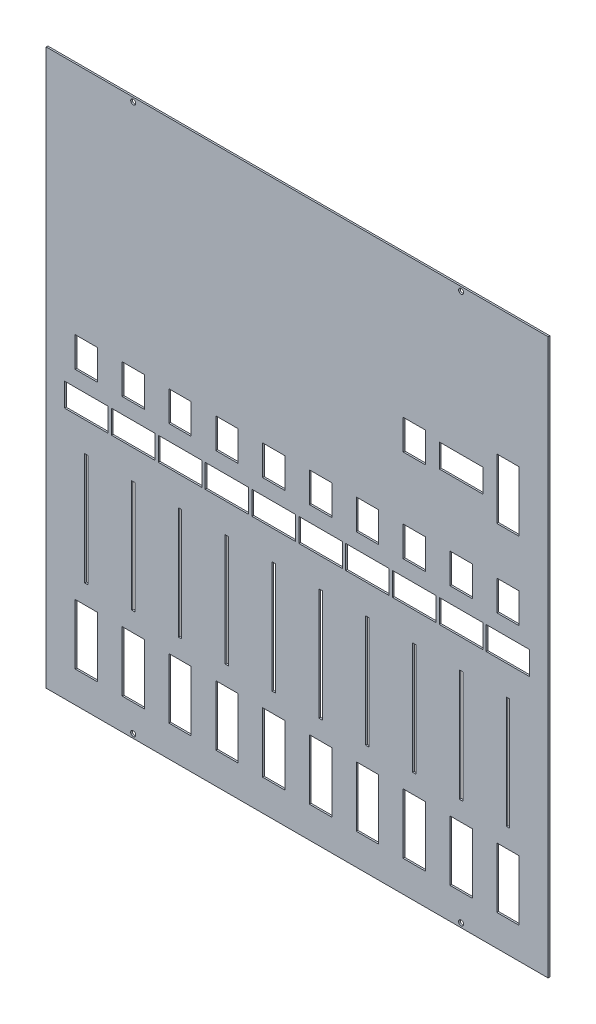
SolidWorks part; units mm, degrees
ref_plane "Front Plane" through (0, 0, 0) normal (0, 0, 1) x (1, 0, 0)
ref_plane "Top Plane" through (0, 0, 0) normal (0, 1, 0) x (1, 0, 0)
ref_plane "Right Plane" through (0, 0, 0) normal (1, 0, 0) x (0, 0, -1)
sketch "Sketch1" plane through (0, 0, 0) normal (0, 0, 1) x (1, 0, 0)
  line L0 (41, 123) -> (43, 123)
  line L1 (-10, 200) -> (290, 200)
  line L2 (-10, 200) -> (-10, -10)
  line L3 (-10, -10) -> (290, -10)
  line L4 (290, 200) -> (290, -10)
  line L5 (7.835, 181.225) -> (20.185, 181.225)
  line L6 (7.835, 181.225) -> (7.835, 164.225)
  line L7 (7.835, 164.225) -> (20.185, 164.225)
  line L8 (20.185, 181.225) -> (20.185, 164.225)
  line L9 (35.835, 181.225) -> (48.185, 181.225)
  line L10 (35.835, 181.225) -> (35.835, 164.225)
  line L11 (35.835, 164.225) -> (48.185, 164.225)
  line L12 (48.185, 181.225) -> (48.185, 164.225)
  line L13 (63.835, 181.225) -> (76.185, 181.225)
  line L14 (63.835, 181.225) -> (63.835, 164.225)
  line L15 (63.835, 164.225) -> (76.185, 164.225)
  line L16 (76.185, 181.225) -> (76.185, 164.225)
  line L17 (91.835, 181.225) -> (104.185, 181.225)
  line L18 (91.835, 181.225) -> (91.835, 164.225)
  line L19 (91.835, 164.225) -> (104.185, 164.225)
  line L20 (104.185, 181.225) -> (104.185, 164.225)
  line L21 (119.835, 181.225) -> (132.185, 181.225)
  line L22 (119.835, 181.225) -> (119.835, 164.225)
  line L23 (119.835, 164.225) -> (132.185, 164.225)
  line L24 (132.185, 181.225) -> (132.185, 164.225)
  line L25 (147.835, 181.225) -> (160.185, 181.225)
  line L26 (147.835, 181.225) -> (147.835, 164.225)
  line L27 (147.835, 164.225) -> (160.185, 164.225)
  line L28 (160.185, 181.225) -> (160.185, 164.225)
  line L29 (175.835, 181.225) -> (188.185, 181.225)
  line L30 (175.835, 181.225) -> (175.835, 164.225)
  line L31 (175.835, 164.225) -> (188.185, 164.225)
  line L32 (188.185, 181.225) -> (188.185, 164.225)
  line L33 (203.835, 181.225) -> (216.185, 181.225)
  line L34 (203.835, 181.225) -> (203.835, 164.225)
  line L35 (203.835, 164.225) -> (216.185, 164.225)
  line L36 (216.185, 181.225) -> (216.185, 164.225)
  line L37 (231.835, 181.225) -> (244.185, 181.225)
  line L38 (231.835, 181.225) -> (231.835, 164.225)
  line L39 (231.835, 164.225) -> (244.185, 164.225)
  line L40 (244.185, 181.225) -> (244.185, 164.225)
  line L41 (259.835, 181.225) -> (272.185, 181.225)
  line L42 (259.835, 181.225) -> (259.835, 164.225)
  line L43 (259.835, 164.225) -> (272.185, 164.225)
  line L44 (272.185, 181.225) -> (272.185, 164.225)
  line L45 (7.835, 44.125) -> (20.185, 44.125)
  line L46 (7.835, 44.125) -> (7.835, 9.125)
  line L47 (7.835, 9.125) -> (20.185, 9.125)
  line L48 (20.185, 44.125) -> (20.185, 9.125)
  line L49 (35.835, 44.125) -> (48.185, 44.125)
  line L50 (35.835, 44.125) -> (35.835, 9.125)
  line L51 (35.835, 9.125) -> (48.185, 9.125)
  line L52 (48.185, 44.125) -> (48.185, 9.125)
  line L53 (63.835, 44.125) -> (76.185, 44.125)
  line L54 (63.835, 44.125) -> (63.835, 9.125)
  line L55 (63.835, 9.125) -> (76.185, 9.125)
  line L56 (76.185, 44.125) -> (76.185, 9.125)
  line L57 (91.835, 44.125) -> (104.185, 44.125)
  line L58 (91.835, 44.125) -> (91.835, 9.125)
  line L59 (91.835, 9.125) -> (104.185, 9.125)
  line L60 (104.185, 44.125) -> (104.185, 9.125)
  line L61 (119.835, 44.125) -> (132.185, 44.125)
  line L62 (119.835, 44.125) -> (119.835, 9.125)
  line L63 (119.835, 9.125) -> (132.185, 9.125)
  line L64 (132.185, 44.125) -> (132.185, 9.125)
  line L65 (147.835, 44.125) -> (160.185, 44.125)
  line L66 (147.835, 44.125) -> (147.835, 9.125)
  line L67 (147.835, 9.125) -> (160.185, 9.125)
  line L68 (160.185, 44.125) -> (160.185, 9.125)
  line L69 (175.835, 44.125) -> (188.185, 44.125)
  line L70 (175.835, 44.125) -> (175.835, 9.125)
  line L71 (175.835, 9.125) -> (188.185, 9.125)
  line L72 (188.185, 44.125) -> (188.185, 9.125)
  line L73 (203.835, 44.125) -> (216.185, 44.125)
  line L74 (203.835, 44.125) -> (203.835, 9.125)
  line L75 (203.835, 9.125) -> (216.185, 9.125)
  line L76 (216.185, 44.125) -> (216.185, 9.125)
  line L77 (231.835, 9.125) -> (244.185, 9.125)
  line L78 (231.835, 9.125) -> (231.835, 44.125)
  line L79 (231.835, 44.125) -> (244.185, 44.125)
  line L80 (244.185, 9.125) -> (244.185, 44.125)
  line L81 (259.835, 44.125) -> (272.185, 44.125)
  line L82 (259.835, 44.125) -> (259.835, 9.125)
  line L83 (259.835, 9.125) -> (272.185, 9.125)
  line L84 (272.185, 44.125) -> (272.185, 9.125)
  line L85 (13, 123) -> (15, 123)
  line L86 (13, 123) -> (13, 56)
  line L87 (13, 56) -> (15, 56)
  line L88 (15, 123) -> (15, 56)
  line L89 (41, 123) -> (41, 56)
  line L90 (41, 56) -> (43, 56)
  line L91 (43, 123) -> (43, 56)
  line L92 (69, 123) -> (71, 123)
  line L93 (69, 123) -> (69, 56)
  line L94 (69, 56) -> (71, 56)
  line L95 (71, 123) -> (71, 56)
  line L96 (97, 123) -> (99, 123)
  line L97 (97, 123) -> (97, 56)
  line L98 (97, 56) -> (99, 56)
  line L99 (99, 123) -> (99, 56)
  line L100 (125, 123) -> (127, 123)
  line L101 (125, 123) -> (125, 56)
  line L102 (125, 56) -> (127, 56)
  line L103 (127, 123) -> (127, 56)
  line L104 (153, 123) -> (155, 123)
  line L105 (153, 123) -> (153, 56)
  line L106 (153, 56) -> (155, 56)
  line L107 (155, 123) -> (155, 56)
  line L108 (181, 123) -> (183, 123)
  line L109 (181, 123) -> (181, 56)
  line L110 (181, 56) -> (183, 56)
  line L111 (183, 123) -> (183, 56)
  line L112 (209, 123) -> (211, 123)
  line L113 (209, 123) -> (209, 56)
  line L114 (209, 56) -> (211, 56)
  line L115 (211, 123) -> (211, 56)
  line L116 (237, 123) -> (239, 123)
  line L117 (237, 123) -> (237, 56)
  line L118 (237, 56) -> (239, 56)
  line L119 (239, 123) -> (239, 56)
  line L120 (265, 123) -> (267, 123)
  line L121 (265, 123) -> (265, 56)
  line L122 (265, 56) -> (267, 56)
  line L123 (267, 123) -> (267, 56)
  line L125 (1.5, 154) -> (26.5, 154)
  line L126 (1.5, 154) -> (1.5, 141)
  line L127 (1.5, 141) -> (26.5, 141)
  line L128 (26.5, 154) -> (26.5, 141)
  line L129 (29.5, 154) -> (54.5, 154)
  line L130 (29.5, 154) -> (29.5, 141)
  line L131 (29.5, 141) -> (54.5, 141)
  line L132 (54.5, 154) -> (54.5, 141)
  line L133 (57.5, 154) -> (82.5, 154)
  line L134 (57.5, 154) -> (57.5, 141)
  line L135 (57.5, 141) -> (82.5, 141)
  line L136 (82.5, 154) -> (82.5, 141)
  line L137 (85.5, 154) -> (110.5, 154)
  line L138 (85.5, 154) -> (85.5, 141)
  line L139 (85.5, 141) -> (110.5, 141)
  line L140 (110.5, 154) -> (110.5, 141)
  line L141 (113.5, 154) -> (138.5, 154)
  line L142 (113.5, 154) -> (113.5, 141)
  line L143 (113.5, 141) -> (138.5, 141)
  line L144 (138.5, 154) -> (138.5, 141)
  line L145 (141.5, 154) -> (166.5, 154)
  line L146 (141.5, 154) -> (141.5, 141)
  line L147 (141.5, 141) -> (166.5, 141)
  line L148 (166.5, 154) -> (166.5, 141)
  line L149 (169.5, 154) -> (194.5, 154)
  line L150 (169.5, 154) -> (169.5, 141)
  line L151 (169.5, 141) -> (194.5, 141)
  line L152 (194.5, 154) -> (194.5, 141)
  line L153 (197.5, 154) -> (222.5, 154)
  line L154 (197.5, 154) -> (197.5, 141)
  line L155 (197.5, 141) -> (222.5, 141)
  line L156 (222.5, 154) -> (222.5, 141)
  line L157 (225.5, 154) -> (250.5, 154)
  line L158 (225.5, 154) -> (225.5, 141)
  line L159 (225.5, 141) -> (250.5, 141)
  line L160 (250.5, 154) -> (250.5, 141)
  line L161 (253.5, 154) -> (278.5, 154)
  line L162 (253.5, 154) -> (253.5, 141)
  line L163 (253.5, 141) -> (278.5, 141)
  line L164 (278.5, 154) -> (278.5, 141)
  dimension "D1" = 10
extrude "Boss-Extrude1" add sketch "Sketch1" along normal blind 1
sketch "Sketch2" plane through (0, 0, 1) normal (0, 0, 1) x (1, 0, 0)
sketch "Sketch3" plane through (0, 0, 1) normal (0, 0, 1) x (1, 0, 0)
  line L0 (290, 200) -> (290, 266)
  line L1 (290, 266) -> (-10, 266)
  line L2 (-10, 266) -> (-10, 200)
  line L3 (-10, 200) -> (290, 200)
  line L5 (225.5, 223.35) -> (250.5, 223.35)
  line L6 (225.5, 223.35) -> (225.5, 236.35)
  line L7 (225.5, 236.35) -> (250.5, 236.35)
  line L8 (250.5, 223.35) -> (250.5, 236.35)
  line L9 (259.825, 245.5) -> (272.175, 245.5)
  line L10 (259.825, 245.5) -> (259.825, 210.5)
  line L11 (259.825, 210.5) -> (272.175, 210.5)
  line L12 (272.175, 245.5) -> (272.175, 210.5)
extrude "Boss-Extrude2" add sketch "Sketch3" against normal blind 0.5 contours L2 L3 L0 L1 L8 L5 L6 L7 L9 L12 L11 L10
sketch "Sketch13" plane through (0, 0, 1) normal (0, 0, 1) x (1, 0, 0)
  line L0 (259.825, 245.5) -> (203.825, 245.5)
  line L1 (203.825, 245.5) -> (203.825, 232.9156)
  line L2 (203.825, 232.9156) -> (216.175, 232.9156)
  line L3 (259.825, 228) -> (216.175, 228)
  line L4 (259.825, 245.5) -> (259.825, 210.5) construction
  line L5 (216.175, 228) -> (216.175, 236.5)
  line L6 (216.175, 236.5) -> (203.825, 236.5)
  line L7 (203.825, 236.5) -> (203.825, 219.5)
  line L8 (203.825, 219.5) -> (216.175, 219.5)
  line L9 (216.175, 219.5) -> (216.175, 228)
extrude "Cut-Extrude4" cut sketch "Sketch13" against normal blind 15 contours L8 L9 L5 L2 L7 | L5 L6 L1 L2
sketch "Sketch14" plane through (0, 0, 1) normal (0, 0, 1) x (1, 0, 0)
  line L0 (7.835, 181.225) -> (7.835, 181.725)
  line L1 (7.835, 181.725) -> (20.685, 181.725)
  line L2 (20.685, 181.725) -> (20.685, 163.725)
  line L3 (20.685, 163.725) -> (7.335, 163.725)
  line L4 (7.335, 163.725) -> (7.335, 181.725)
  line L5 (7.335, 181.725) -> (7.835, 181.725)
  line L6 (35.835, 181.225) -> (35.835, 181.725)
  line L7 (35.835, 181.725) -> (48.685, 181.725)
  line L8 (48.685, 181.725) -> (48.685, 163.725)
  line L9 (48.685, 163.725) -> (35.335, 163.725)
  line L10 (35.335, 163.725) -> (35.335, 181.725)
  line L11 (35.335, 181.725) -> (35.835, 181.725)
  line L12 (63.835, 181.225) -> (63.835, 181.725)
  line L13 (63.835, 181.725) -> (76.685, 181.725)
  line L14 (76.685, 181.725) -> (76.685, 163.725)
  line L15 (76.685, 163.725) -> (63.335, 163.725)
  line L16 (63.335, 163.725) -> (63.335, 181.725)
  line L17 (63.335, 181.725) -> (63.835, 181.725)
  line L18 (91.835, 181.225) -> (91.835, 181.725)
  line L19 (91.835, 181.725) -> (104.685, 181.725)
  line L20 (104.685, 181.725) -> (104.685, 163.725)
  line L21 (104.685, 163.725) -> (91.335, 163.725)
  line L22 (91.335, 163.725) -> (91.335, 181.725)
  line L23 (91.335, 181.725) -> (91.835, 181.725)
  line L24 (119.835, 181.225) -> (119.835, 181.725)
  line L25 (119.835, 181.725) -> (132.685, 181.725)
  line L26 (132.685, 181.725) -> (132.685, 163.725)
  line L27 (132.685, 163.725) -> (119.335, 163.725)
  line L28 (119.335, 163.725) -> (119.335, 181.725)
  line L29 (119.335, 181.725) -> (119.835, 181.725)
  line L30 (147.835, 181.225) -> (147.835, 181.725)
  line L31 (147.835, 181.725) -> (160.685, 181.725)
  line L32 (160.685, 181.725) -> (160.685, 163.725)
  line L33 (160.685, 163.725) -> (147.335, 163.725)
  line L34 (147.335, 163.725) -> (147.335, 181.725)
  line L35 (147.335, 181.725) -> (147.835, 181.725)
  line L36 (175.835, 181.225) -> (175.835, 181.725)
  line L37 (175.835, 181.725) -> (188.685, 181.725)
  line L38 (188.685, 181.725) -> (188.685, 163.725)
  line L39 (188.685, 163.725) -> (175.335, 163.725)
  line L40 (175.335, 163.725) -> (175.335, 181.725)
  line L41 (175.335, 181.725) -> (175.835, 181.725)
  line L42 (203.835, 181.225) -> (203.835, 181.725)
  line L43 (203.835, 181.725) -> (216.685, 181.725)
  line L44 (216.685, 181.725) -> (216.685, 163.725)
  line L45 (216.685, 163.725) -> (203.335, 163.725)
  line L46 (203.335, 163.725) -> (203.335, 181.725)
  line L47 (203.335, 181.725) -> (203.835, 181.725)
  line L48 (231.835, 181.225) -> (231.835, 181.725)
  line L49 (231.835, 181.725) -> (244.685, 181.725)
  line L50 (244.685, 181.725) -> (244.685, 163.725)
  line L51 (244.685, 163.725) -> (231.335, 163.725)
  line L52 (231.335, 163.725) -> (231.335, 181.725)
  line L53 (231.335, 181.725) -> (231.835, 181.725)
  line L54 (259.835, 181.225) -> (259.835, 181.725)
  line L55 (259.835, 181.725) -> (272.685, 181.725)
  line L56 (272.685, 181.725) -> (272.685, 163.725)
  line L57 (272.685, 163.725) -> (259.335, 163.725)
  line L58 (259.335, 163.725) -> (259.335, 181.725)
  line L59 (259.335, 181.725) -> (259.835, 181.725)
  dimension "D1" = 10
extrude "Cut-Extrude5" cut sketch "Sketch14" against normal blind 10
sketch "Sketch15" plane through (0, 0, 1) normal (0, 0, 1) x (1, 0, 0)
  line L0 (7.835, 44.125) -> (7.835, 44.625)
  line L1 (7.835, 44.625) -> (20.685, 44.625)
  line L2 (20.685, 44.625) -> (20.685, 8.625)
  line L3 (20.685, 8.625) -> (7.335, 8.625)
  line L4 (7.335, 8.625) -> (7.335, 44.625)
  line L5 (7.335, 44.625) -> (7.835, 44.625)
  line L6 (35.835, 44.625) -> (48.685, 44.625)
  line L7 (35.335, 8.625) -> (35.335, 44.625)
  line L8 (48.685, 8.625) -> (35.335, 8.625)
  line L9 (48.685, 44.625) -> (48.685, 8.625)
  line L10 (35.335, 44.625) -> (35.835, 44.625)
  line L11 (63.835, 44.625) -> (76.685, 44.625)
  line L12 (63.335, 8.625) -> (63.335, 44.625)
  line L13 (76.685, 8.625) -> (63.335, 8.625)
  line L14 (76.685, 44.625) -> (76.685, 8.625)
  line L15 (63.335, 44.625) -> (63.835, 44.625)
  line L16 (91.835, 44.625) -> (104.685, 44.625)
  line L17 (91.335, 8.625) -> (91.335, 44.625)
  line L18 (104.685, 8.625) -> (91.335, 8.625)
  line L19 (104.685, 44.625) -> (104.685, 8.625)
  line L20 (91.335, 44.625) -> (91.835, 44.625)
  line L21 (119.835, 44.625) -> (132.685, 44.625)
  line L22 (119.335, 8.625) -> (119.335, 44.625)
  line L23 (132.685, 8.625) -> (119.335, 8.625)
  line L24 (132.685, 44.625) -> (132.685, 8.625)
  line L25 (119.335, 44.625) -> (119.835, 44.625)
  line L26 (147.835, 44.625) -> (160.685, 44.625)
  line L27 (147.335, 8.625) -> (147.335, 44.625)
  line L28 (160.685, 8.625) -> (147.335, 8.625)
  line L29 (160.685, 44.625) -> (160.685, 8.625)
  line L30 (147.335, 44.625) -> (147.835, 44.625)
  line L31 (175.835, 44.625) -> (188.685, 44.625)
  line L32 (175.335, 8.625) -> (175.335, 44.625)
  line L33 (188.685, 8.625) -> (175.335, 8.625)
  line L34 (188.685, 44.625) -> (188.685, 8.625)
  line L35 (175.335, 44.625) -> (175.835, 44.625)
  line L36 (203.835, 44.625) -> (216.685, 44.625)
  line L37 (203.335, 8.625) -> (203.335, 44.625)
  line L38 (216.685, 8.625) -> (203.335, 8.625)
  line L39 (216.685, 44.625) -> (216.685, 8.625)
  line L40 (203.335, 44.625) -> (203.835, 44.625)
  line L41 (231.835, 44.625) -> (244.685, 44.625)
  line L42 (231.335, 8.625) -> (231.335, 44.625)
  line L43 (244.685, 8.625) -> (231.335, 8.625)
  line L44 (244.685, 44.625) -> (244.685, 8.625)
  line L45 (231.335, 44.625) -> (231.835, 44.625)
  line L46 (259.835, 44.625) -> (272.685, 44.625)
  line L47 (259.335, 8.625) -> (259.335, 44.625)
  line L48 (272.685, 8.625) -> (259.335, 8.625)
  line L49 (272.685, 44.625) -> (272.685, 8.625)
  line L50 (259.335, 44.625) -> (259.835, 44.625)
  dimension "D1" = 10
extrude "Cut-Extrude6" cut sketch "Sketch15" against normal blind 10
sketch "Sketch16" plane through (0, 0, 1) normal (0, 0, 1) x (1, 0, 0)
  line L0 (1.5, 154) -> (1.5, 154.5)
  line L1 (1.5, 154.5) -> (27, 154.5)
  line L2 (27, 154.5) -> (27, 140.5)
  line L3 (27, 140.5) -> (1, 140.5)
  line L4 (1, 140.5) -> (1, 154.5)
  line L5 (1, 154.5) -> (1.5, 154.5)
  line L6 (29.5, 154) -> (29.5, 154.5)
  line L7 (29.5, 154.5) -> (55, 154.5)
  line L8 (55, 154.5) -> (55, 140.5)
  line L9 (55, 140.5) -> (29, 140.5)
  line L10 (29, 140.5) -> (29, 154.5)
  line L11 (29, 154.5) -> (29.5, 154.5)
  line L12 (57.5, 154) -> (57.5, 154.5)
  line L13 (57.5, 154.5) -> (83, 154.5)
  line L14 (83, 154.5) -> (83, 140.5)
  line L15 (83, 140.5) -> (57, 140.5)
  line L16 (57, 140.5) -> (57, 154.5)
  line L17 (57, 154.5) -> (57.5, 154.5)
  line L18 (85.5, 154) -> (85.5, 154.5)
  line L19 (85.5, 154.5) -> (111, 154.5)
  line L20 (111, 154.5) -> (111, 140.5)
  line L21 (111, 140.5) -> (85, 140.5)
  line L22 (85, 140.5) -> (85, 154.5)
  line L23 (85, 154.5) -> (85.5, 154.5)
  line L24 (113.5, 154) -> (113.5, 154.5)
  line L25 (113.5, 154.5) -> (139, 154.5)
  line L26 (139, 154.5) -> (139, 140.5)
  line L27 (139, 140.5) -> (113, 140.5)
  line L28 (113, 140.5) -> (113, 154.5)
  line L29 (113, 154.5) -> (113.5, 154.5)
  line L30 (141.5, 154) -> (141.5, 154.5)
  line L31 (141.5, 154.5) -> (167, 154.5)
  line L32 (167, 154.5) -> (167, 140.5)
  line L33 (167, 140.5) -> (141, 140.5)
  line L34 (141, 140.5) -> (141, 154.5)
  line L35 (141, 154.5) -> (141.5, 154.5)
  line L36 (169.5, 154) -> (169.5, 154.5)
  line L37 (169.5, 154.5) -> (195, 154.5)
  line L38 (195, 154.5) -> (195, 140.5)
  line L39 (195, 140.5) -> (169, 140.5)
  line L40 (169, 140.5) -> (169, 154.5)
  line L41 (169, 154.5) -> (169.5, 154.5)
  line L42 (197.5, 154) -> (197.5, 154.5)
  line L43 (197.5, 154.5) -> (223, 154.5)
  line L44 (223, 154.5) -> (223, 140.5)
  line L45 (223, 140.5) -> (197, 140.5)
  line L46 (197, 140.5) -> (197, 154.5)
  line L47 (197, 154.5) -> (197.5, 154.5)
  line L48 (225.5, 154) -> (225.5, 154.5)
  line L49 (225.5, 154.5) -> (251, 154.5)
  line L50 (251, 154.5) -> (251, 140.5)
  line L51 (251, 140.5) -> (225, 140.5)
  line L52 (225, 140.5) -> (225, 154.5)
  line L53 (225, 154.5) -> (225.5, 154.5)
  line L54 (253.5, 154) -> (253.5, 154.5)
  line L55 (253.5, 154.5) -> (279, 154.5)
  line L56 (279, 154.5) -> (279, 140.5)
  line L57 (279, 140.5) -> (253, 140.5)
  line L58 (253, 140.5) -> (253, 154.5)
  line L59 (253, 154.5) -> (253.5, 154.5)
  dimension "D1" = 10
extrude "Cut-Extrude7" cut sketch "Sketch16" against normal blind 10
sketch "Sketch17" plane through (0, 0, 1) normal (0, 0, 1) x (1, 0, 0)
  line L0 (203.825, 236.5) -> (203.825, 237)
  line L1 (203.825, 237) -> (216.675, 237)
  line L2 (216.675, 237) -> (216.675, 219)
  line L3 (216.675, 219) -> (203.325, 219)
  line L4 (203.325, 219) -> (203.325, 237)
  line L5 (203.325, 237) -> (203.825, 237)
  line L6 (259.825, 245.5) -> (259.825, 246)
  line L7 (259.825, 246) -> (272.675, 246)
  line L8 (272.675, 246) -> (272.675, 210)
  line L9 (272.675, 210) -> (259.325, 210)
  line L10 (259.325, 210) -> (259.325, 246)
  line L11 (259.325, 246) -> (259.825, 246)
extrude "Cut-Extrude8" cut sketch "Sketch17" against normal blind 10
sketch "Sketch18" plane through (0, 0, 1) normal (0, 0, 1) x (1, 0, 0)
  line L0 (216.675, 228) -> (259.325, 228)
  line L1 (216.675, 237) -> (216.675, 219) construction
  line L2 (259.325, 210) -> (259.325, 246) construction
  line L3 (250.5, 223.35) -> (250.5, 228)
  line L4 (250.5, 223.35) -> (250.5, 236.35) construction
  line L5 (250.5, 228) -> (251, 228)
  line L6 (238, 228) -> (238, 221)
  line L7 (238, 221) -> (251, 221)
  line L8 (251, 221) -> (251, 228)
  line L9 (238, 221) -> (225, 221)
  line L10 (225, 221) -> (225, 228)
  line L11 (225, 228) -> (225, 235)
  line L12 (225, 235) -> (251, 235)
  line L13 (251, 235) -> (251, 228)
extrude "Cut-Extrude9" cut sketch "Sketch18" against normal blind 10
sketch "Sketch19" plane through (0, 0, 1) normal (0, 0, 1) x (1, 0, 0)
  line L0 (225.5, 235) -> (250.5, 235)
  line L1 (225.5, 235) -> (225.5, 236.2576)
  line L2 (250.5, 235) -> (250.5, 236.2576)
  line L3 (225.5, 236.2576) -> (250.5, 236.2576)
extrude "Boss-Extrude7" add sketch "Sketch19" against normal blind 0.5
sketch "Sketch20" plane through (0, 0, 1) normal (0, 0, 1) x (1, 0, 0)
  line L0 (224.4374, 237.361) -> (251.6124, 237.6688)
  line L1 (224.4374, 237.361) -> (224.4577, 235.5651)
  line L2 (251.6124, 237.6688) -> (251.6328, 235.873)
  line L3 (224.4577, 235.5651) -> (251.6328, 235.873)
extrude "Boss-Extrude8" add sketch "Sketch20" against normal blind 0.5
sketch "Sketch21" plane through (0, 0, 0.5) normal (0, 0, -1) x (-1, 0, 0)
  line L0 (-290, 266) -> (-290, 200)
  line L1 (-290, 200) -> (10, 200)
  line L2 (10, 266) -> (10, 200) construction
  line L3 (10, 200) -> (-290, 200) construction
  line L4 (10, 200) -> (10, 266)
  line L5 (10, 266) -> (-290, 266)
  line L6 (-272.675, 246) -> (-272.675, 210)
  line L7 (-272.675, 246) -> (-259.325, 246)
  line L8 (-272.675, 210) -> (-259.325, 210)
  line L9 (-259.325, 246) -> (-259.325, 210)
  line L10 (-251, 235) -> (-225, 235)
  line L11 (-251, 235) -> (-251, 221)
  line L12 (-225, 235) -> (-225, 221)
  line L13 (-251, 221) -> (-225, 221)
  line L14 (-216.675, 237) -> (-203.325, 237)
  line L15 (-216.675, 237) -> (-216.675, 219)
  line L16 (-203.325, 237) -> (-203.325, 219)
  line L17 (-216.675, 219) -> (-203.325, 219)
  line M17 (-272.675, 210) -> (-272.675, 246)
  line M18 (-272.675, 246) -> (-259.325, 246)
  line M19 (-259.325, 246) -> (-259.325, 210)
  line M20 (-259.325, 210) -> (-272.675, 210)
  line M21 (10, 200) -> (10, 266)
  line M22 (10, 266) -> (-290, 266)
  line M23 (-290, 266) -> (-290, 200)
  line M24 (-290, 200) -> (10, 200)
  line M25 (-216.675, 219) -> (-216.675, 237)
  line M26 (-216.675, 237) -> (-203.325, 237)
  line M27 (-203.325, 237) -> (-203.325, 219)
  line M28 (-203.325, 219) -> (-216.675, 219)
  line M29 (-251, 235) -> (-225, 235)
  line M30 (-225, 235) -> (-225, 221)
  line M31 (-225, 221) -> (-251, 221)
  line M32 (-251, 221) -> (-251, 235)
extrude "Boss-Extrude11" add sketch "Sketch21" along normal blind 0.5 contours M24 M21 M22 M23 M28 M25 M26 M27 M32 M29 M30 M31 M20 M17 M18 M19
sketch "Sketch22" plane through (0, 0, 0) normal (0, 0, -1) x (-1, 0, 0)
  line L0 (-290, 266) -> (-290, 322)
  line L1 (-290, 322) -> (10, 322)
  line L2 (10, 322) -> (10, 266)
  line L3 (-290, 266) -> (10, 266)
extrude "Boss-Extrude12" add sketch "Sketch22" against normal blind 1
sketch "Sketch23" plane through (0, 0, 0) normal (0, 0, -1) x (-1, 0, 0)
  line L0 (-238.01, 8.625) -> (-238.01, -10)
  line L1 (-244.685, 8.625) -> (-231.335, 8.625) construction
  line L2 (10, -10) -> (-290, -10) construction
  line L3 (-238.01, -10) -> (-238.01, -7.5)
  line L4 (-140, -10) -> (-140, 21.317)
  line L5 (-41.99, -10) -> (-41.99, -7.5)
  line L6 (-41.99, 8.625) -> (-41.99, -10)
  circle A0 centre (-238.01, -7.5) radius 1.5
  circle A1 centre (-41.99, -7.5) radius 1.5
extrude "Cut-Extrude10" cut sketch "Sketch23" against normal blind 1 contours L0 A0 | L0 A0 | A1 L6 | A1 L6
sketch "Sketch24" plane through (0, 0, 0) normal (0, 0, -1) x (-1, 0, 0)
  line L0 (-238.01, -7.5) -> (-238.01, 322)
  line L1 (10, 322) -> (-290, 322) construction
  line L2 (-238.01, 322) -> (-238.01, 319.5)
  line L3 (-140, 322) -> (-140, 311.0135)
  circle A0 centre (-238.01, 319.5) radius 1.5
  circle A1 centre (-41.99, 319.5) radius 1.5
extrude "Cut-Extrude11" cut sketch "Sketch24" against normal blind 1 contours L0 A0 | L0 A0 | A1
